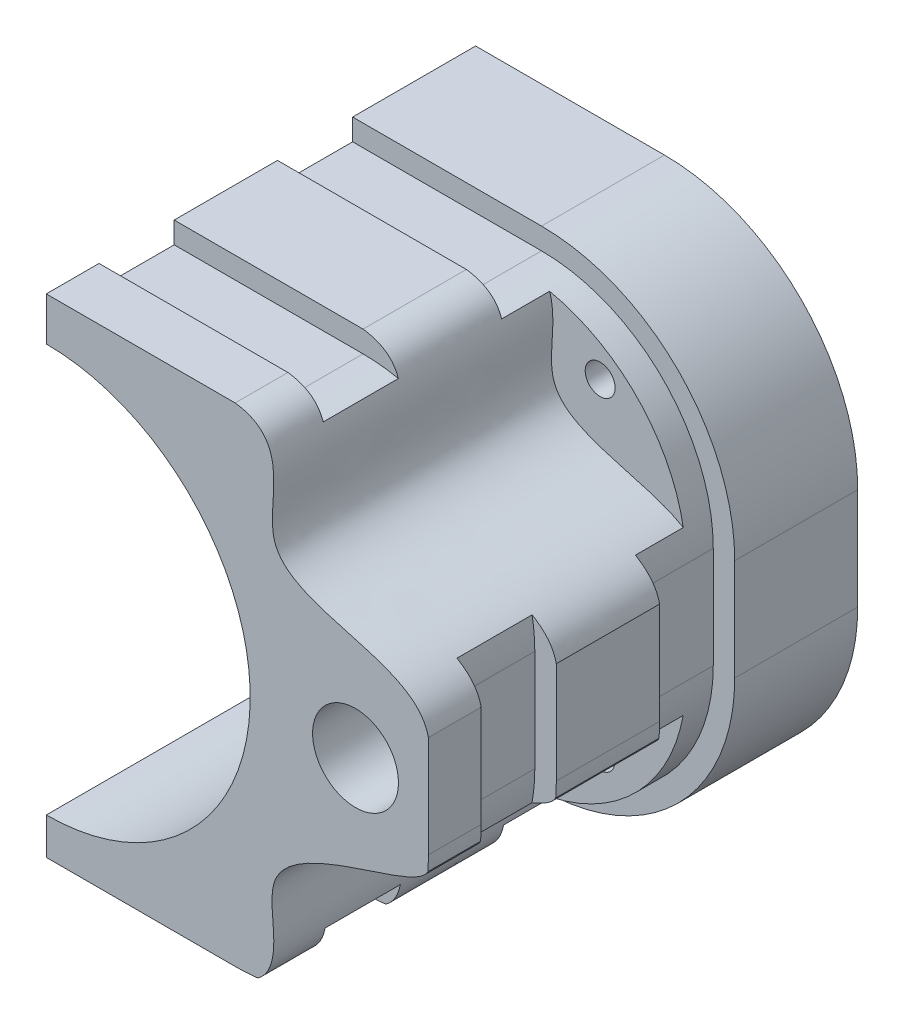
SolidWorks part; units mm, degrees
ref_plane "Plano frontal" through (0, 0, 0) normal (0, 0, 1) x (1, 0, 0)
ref_plane "Plano superior" through (0, 0, 0) normal (0, 1, 0) x (1, 0, 0)
ref_plane "Plano direito" through (0, 0, 0) normal (1, 0, 0) x (0, 0, -1)
sketch "Esboço1" plane through (0, 0, 0) normal (0, 0, 1) x (1, 0, 0)
  line L2 (-90, -22.4239) -> (-90, -19)
  line L6 (-90, 19) -> (-90, 23.0425)
  line L7 (-90, 23.0425) -> (-72.4018, 23.0425)
  line L8 (-54.4018, 5.0425) -> (-54.4018, -4.4239)
  line L9 (-90, -22.4239) -> (-72.4018, -22.4239)
  arc A0 (-90, -19) -> (-90, 19) centre (-90, 0) ccw
  circle A3 centre (-64.3997, 15.9483) radius 1.3931
  circle A4 centre (-61.1894, 0) radius 4
  arc A5 (-72.4018, 23.0425) -> (-54.4018, 5.0425) centre (-72.4018, 5.0425) cw
  arc A6 (-54.4018, -4.4239) -> (-72.4018, -22.4239) centre (-72.4018, -4.4239) cw
  circle A7 centre (-64.3997, -14.2289) radius 1.3706
  point P1 (-90, 0)
  dimension "D5" = 18
extrude "Ressalto-extrusão1" add sketch "Esboço1" along normal blind 40 contours A0 L6 L7 A5 L8 A6 L9 L2 | A7 | A4 | A3
sketch "Esboço5" plane through (0, 0, 40) normal (0, 0, 1) x (1, 0, 0)
  line L0 (-90.5617, 0) -> (-21.8603, 0) construction
  circle A0 centre (-64.3997, 15.9483) radius 1.3931 construction
  circle A1 centre (-64.3997, -14.2289) radius 1.3706 construction
  arc A2 (-54.4018, 5.0425) -> (-72.4018, 23.0425) centre (-72.4018, 5.0425) ccw construction
  arc A3 (-72.4018, -22.4239) -> (-54.4018, -4.4239) centre (-72.4018, -4.4239) ccw construction
  circle A4 centre (-64.3997, 15.9483) radius 1.3931
  circle A5 centre (-64.3997, -14.2289) radius 1.3706
  arc A6 (-54.4018, 5.0425) -> (-72.4018, 23.0425) centre (-72.4018, 5.0425) ccw
  arc A7 (-70.293, -22.2999) -> (-54.4551, -5.8084) centre (-72.4018, -4.4239) ccw
  spline S0 degree 3 poles (-54.4018, 5.0425) (-55.53, 10.3838) (-70.4539, 8.6368) (-68.3172, 19.152) (-69.4195, 22.6554) (-72.4018, 23.0425) knots 0 0 0 0 0.598412 0.778329 1 1 1 1
  spline S1 degree 3 poles (-54.4551, -5.8084) (-55.0216, -6.906) (-60.8246, -8.6574) (-69.9974, -12.0304) (-68.625, -17.5526) (-68.9475, -20.7122) (-69.6515, -21.8472) (-70.293, -22.2999) knots 0.054308 0.054308 0.054308 0.054308 0.30314 0.598412 0.778329 0.849346 0.932733 0.932733 0.932733 0.932733
  arc M4 (-72.4018, -22.4239) -> (-54.4018, -4.4239) centre (-72.4018, -4.4239) ccw
  arc M6 (-54.4018, 5.0425) -> (-72.4018, 23.0425) centre (-72.4018, 5.0425) ccw
  circle M10 centre (-64.3997, -14.2289) radius 1.3706
  circle M11 centre (-64.3997, 15.9483) radius 1.3931
extrude "Corte-extrusão1" cut sketch "Esboço5" against normal blind 26 contours S0 M6 M11 | S1 M4 M10 | A4
sketch "Esboço7" plane through (0, 0, 40) normal (0, 0, 1) x (1, 0, 0)
  line L5 (-54.4018, -4.4239) -> (-54.4018, 5.0425)
  line L6 (-72.4018, 23.0425) -> (-90, 23.0425)
  line L7 (-90, 23.0425) -> (-90, 19)
  line L8 (-90, -19) -> (-90, -22.4239)
  line L9 (-90, -22.4239) -> (-72.4018, -22.4239)
  line L10 (-54.4018, -4.4239) -> (-54.4018, 5.0425)
  line L11 (-72.4018, 23.0425) -> (-90, 23.0425)
  line L14 (-90, -22.4239) -> (-72.4018, -22.4239)
  arc A0 (-54.4018, 5.0425) -> (-72.4018, 23.0425) centre (-72.4018, 5.0425) ccw construction
  arc A1 (-70.293, -22.2999) -> (-54.4551, -5.8084) centre (-72.4018, -4.4239) ccw construction
  arc A2 (-54.4018, 5.0425) -> (-72.4018, 23.0425) centre (-72.4018, 5.0425) ccw
  arc A3 (-90, -19) -> (-90, 19) centre (-90, 0) ccw
  arc A4 (-72.4018, -22.4239) -> (-70.293, -22.2999) centre (-72.4018, -4.4239) ccw
  arc A5 (-54.4551, -5.8084) -> (-54.4018, -4.4239) centre (-72.4018, -4.4239) ccw
  arc A6 (-70.293, -22.2999) -> (-54.4551, -5.8084) centre (-72.4018, -4.4239) ccw
  arc A7 (-72.4018, -22.4239) -> (-70.293, -22.2999) centre (-72.4018, -4.4239) ccw
  arc A8 (-54.4551, -5.8084) -> (-54.4018, -4.4239) centre (-72.4018, -4.4239) ccw
  spline S2 degree 3 poles (-874.5966, -567.0331) (102.3374, 71.6396) (-74.3018, -10.3004) (-65.2525, 34.2349) (-102.3028, 38.506) (-909.8497, -523.451) knots -1.800936 -1.800936 -1.800936 -1.800936 0.598412 0.778329 2.434398 2.434398 2.434398 2.434398 only from (-54.4018, 5.0425) to (-72.4018, 23.0425)
  spline S3 degree 3 poles (-930.8651, 487.0271) (-135.4348, -13.3865) (-70.3907, -34.8539) (-68.625, -17.5526) (-69.9974, -12.0304) (-38.4143, -0.4168) (-28.8151, -3.7982) (-1026.723, 228.0125) knots -1.442026 -1.442026 -1.442026 -1.442026 0.137695 0.208712 0.388628 0.6839 2.70161 2.70161 2.70161 2.70161 only from (-70.293, -22.2999) to (-54.4551, -5.8084)
  dimension "D1" = 0
sketch "Esboço8" plane through (-90, 0, 0) normal (-1, 0, 0) x (0, 0, 1)
  line L0 (40, 23.0425) -> (0, 23.0425) construction
  line L1 (28.0838, 23.0425) -> (35.0838, 23.0425)
  line L2 (28.0838, 23.0425) -> (28.0838, 21.0425)
  line L3 (28.0838, 21.0425) -> (35.0838, 21.0425)
  line L4 (35.0838, 23.0425) -> (35.0838, 21.0425)
  line L5 (11.4595, 23.0425) -> (18.4595, 23.0425)
  line L6 (11.4595, 23.0425) -> (11.4595, 21.0425)
  line L7 (11.4595, 21.0425) -> (18.4595, 21.0425)
  line L8 (18.4595, 23.0425) -> (18.4595, 21.0425)
  dimension "D1" = 2
  dimension "D2" = 7
  dimension "D3" = 2
  dimension "D4" = 7
  dimension "D5" = 0
sweep "Varredura de corte1" cut profiles "Esboço8" path "Esboço7"
